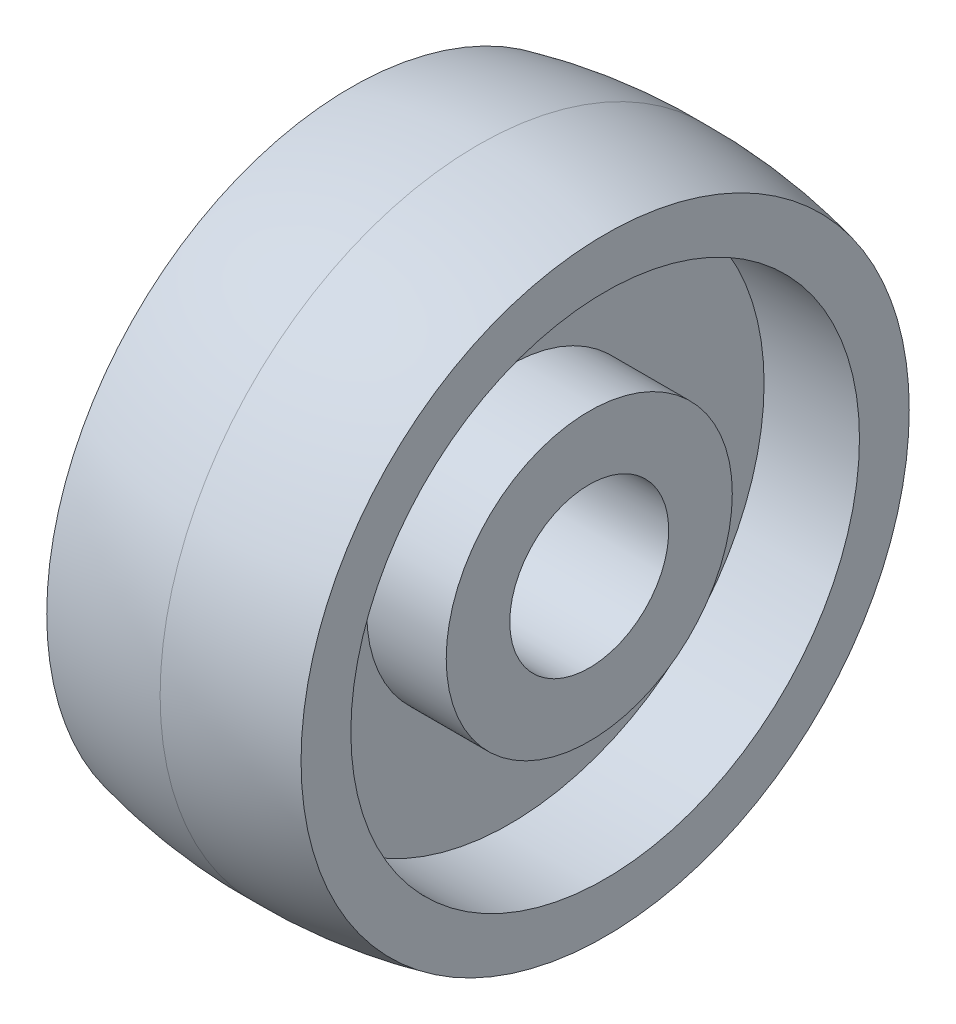
SolidWorks part; units mm, degrees
ref_plane "前视基准面" through (0, 0, 0) normal (0, 0, 1) x (1, 0, 0)
ref_plane "上视基准面" through (0, 0, 0) normal (0, 1, 0) x (1, 0, 0)
ref_plane "右视基准面" through (0, 0, 0) normal (1, 0, 0) x (0, 0, -1)
sketch "草图1" plane through (0, 0, 0) normal (0, 0, 1) x (1, 0, 0)
  line L0 (-14.8052, 0) -> (18.3117, 0) construction
  line L1 (1.7532, 0) -> (1.7532, 20) construction
  line L2 (-5.2468, 5) -> (8.7532, 5)
  line L3 (8.7532, 5) -> (8.7532, 9)
  line L4 (8.7532, 9) -> (3.7532, 9)
  line L5 (3.7532, 9) -> (3.7532, 16)
  line L6 (3.7532, 16) -> (9.7532, 16)
  line L7 (9.7532, 16) -> (9.7532, 19.1332)
  line L8 (-5.2468, 5) -> (-5.2468, 9)
  line L9 (-5.2468, 9) -> (-0.2468, 9)
  line L10 (-0.2468, 9) -> (-0.2468, 16)
  line L11 (-0.2468, 16) -> (-6.2468, 16)
  line L12 (-6.2468, 16) -> (-6.2468, 19.1332)
  arc A0 (9.7532, 19.1332) -> (1.7532, 20) centre (2.1167, -13.9981) ccw
  arc A1 (-6.2468, 19.1332) -> (1.7532, 20) centre (1.3898, -13.9981) cw
  point P14 (1.7532, 5)
  dimension "D6" = 34
  dimension "D7" = 20
  dimension "D1" = 5
  dimension "D2" = 7
  dimension "D3" = 4
  dimension "D4" = 7
  dimension "D5" = 2
  dimension "D8" = 6
revolve "旋转1" add sketch "草图1" angle 360 about L0
